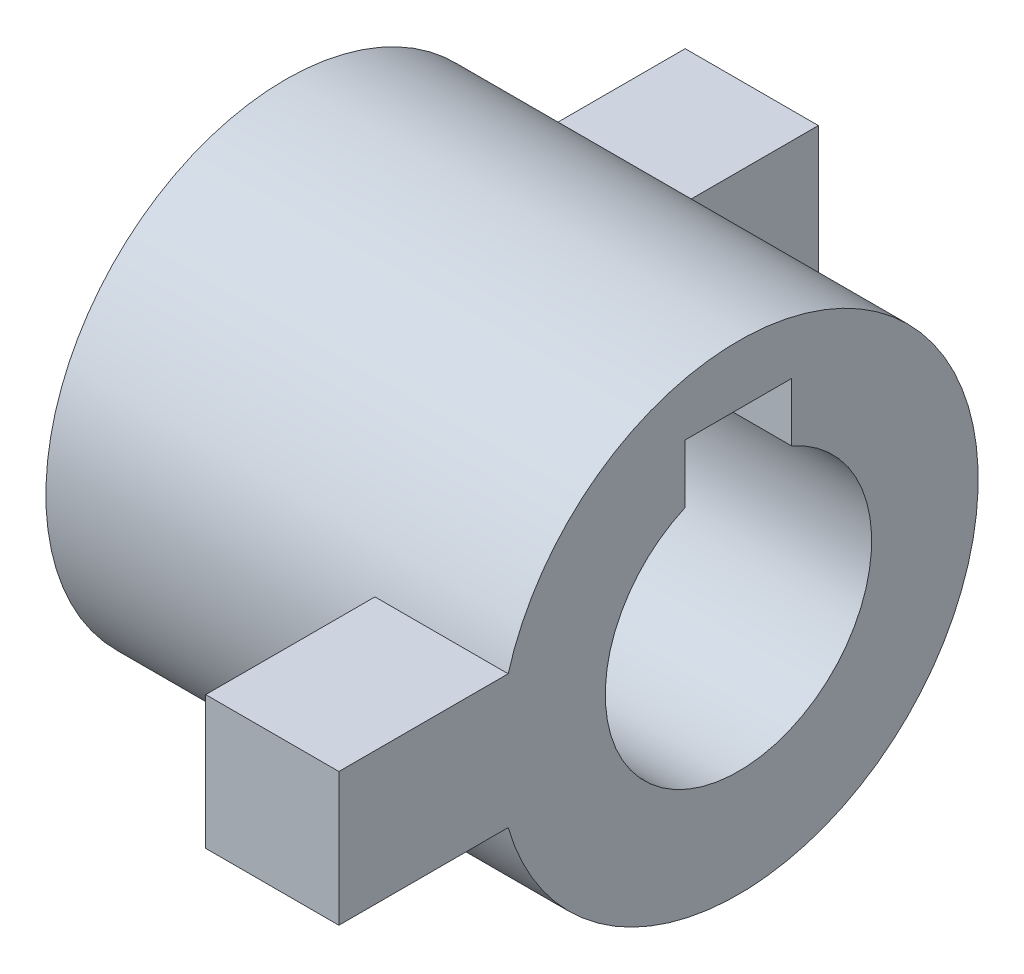
SolidWorks part; units mm, degrees
ref_plane "Front Plane" through (0, 0, 0) normal (0, 0, 1) x (1, 0, 0)
ref_plane "Top Plane" through (0, 0, 0) normal (0, 1, 0) x (1, 0, 0)
ref_plane "Right Plane" through (0, 0, 0) normal (1, 0, 0) x (0, 0, -1)
sketch "Sketch1" plane through (0, 0, 0) normal (1, 0, 0) x (0, 0, -1)
  line L1 (-2, -1.3956) -> (2, -1.3956)
  line L2 (-2, -1.3956) -> (-2, 6.78)
  line L3 (-2, 6.78) -> (2, 6.78)
  line L4 (2, -1.3956) -> (2, 6.78)
  circle A0 centre (0, 0) radius 9
  circle A1 centre (0, 0) radius 5
  point P8 (0, 6.78)
  point P9 (0, 0)
  dimension "D1" = 18
  dimension "D2" = 10
  dimension "D3" = 6.78
  dimension "D4" = 4
extrude "Boss-Extrude1" add sketch "Sketch1" along normal blind 17 contours A0 A1 L2 L3 L4
sketch "Sketch2" plane through (17, 0, 0) normal (1, 0, 0) x (0, 0, -1)
  line L1 (5, 4) -> (20, 4)
  line L2 (5, 4) -> (5, -4)
  line L3 (5, -4) -> (20, -4)
  line L4 (20, 4) -> (20, -4)
  arc A0 (-2, 4.5826) -> (2, 4.5826) centre (0, 0) ccw construction
  point P4 (5, 0)
  dimension "D1" = 8
  dimension "D2" = 15
sketch "Sketch3" plane through (0, 0, 0) normal (0, 1, 0) x (1, 0, 0)
  line L0 (0, 0) -> (17, 0) construction
  line L2 (0, 0) -> (5, 0)
  line L3 (0, 0) -> (0, 15)
  line L4 (0, 15) -> (5, 15)
  line L5 (5, 0) -> (5, 15)
  line L6 (12, 0) -> (17, 0)
  line L7 (12, 0) -> (12, -15)
  line L8 (12, -15) -> (17, -15)
  line L9 (17, 0) -> (17, -15)
  dimension "D1" = 5
  dimension "D2" = 5
  dimension "D3" = 17
  dimension "D4" = 15
  dimension "D5" = 15
extrude "Boss-Extrude3" add sketch "Sketch3" along normal blind 2.5
ref_plane "Plane1" through (0, 0, 0) normal (0, -1, 0) x (-1, 0, 0)
mirror "Mirror1" about plane through (0, 0, 0) normal (0, -1, 0) of "Boss-Extrude3"
sketch "Sketch4" plane through (0, 0, 0) normal (-1, 0, 0) x (0, 0, 1)
  circle A0 centre (0, 0) radius 5
extrude "Cut-Extrude1" cut sketch "Sketch4" against normal through all
